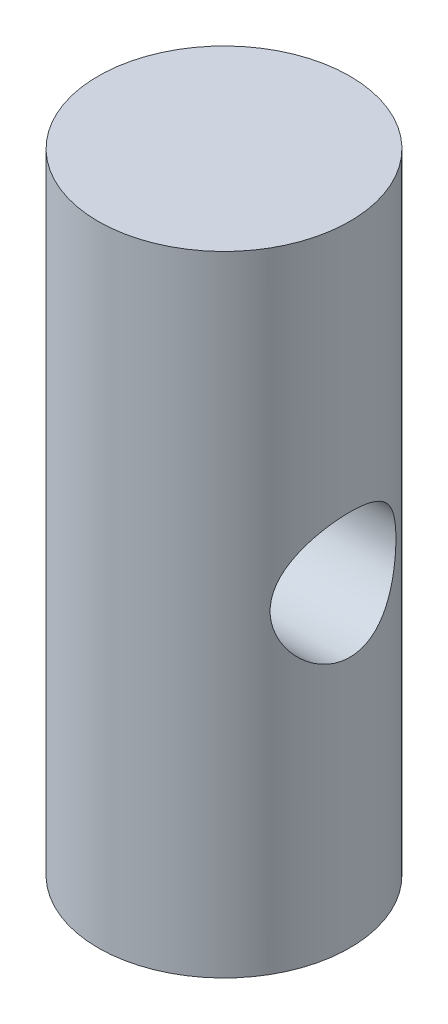
SolidWorks part; units mm, degrees
ref_plane "Front Plane" through (0, 0, 0) normal (0, 0, 1) x (1, 0, 0)
ref_plane "Top Plane" through (0, 0, 0) normal (0, 1, 0) x (1, 0, 0)
ref_plane "Right Plane" through (0, 0, 0) normal (1, 0, 0) x (0, 0, -1)
sketch "Sketch1" plane through (0, 0, 0) normal (0, 1, 0) x (1, 0, 0)
  circle A0 centre (0, 0) radius 5
  dimension "D1" = 10
extrude "Boss-Extrude1" add sketch "Sketch1" along normal blind 25 contours A0
sketch "Sketch2" plane through (0, 0, 0) normal (1, 0, 0) x (0, 0, -1)
  line L0 (0, 0) -> (0, 25) construction
  line L1 (-5, 0) -> (5, 0) construction
  line L2 (5, 25) -> (-5, 25) construction
  circle A0 centre (0, 12.5) radius 2.5
  dimension "D1" = 5
extrude "Cut-Extrude1" cut sketch "Sketch2" against normal mid plane 10
